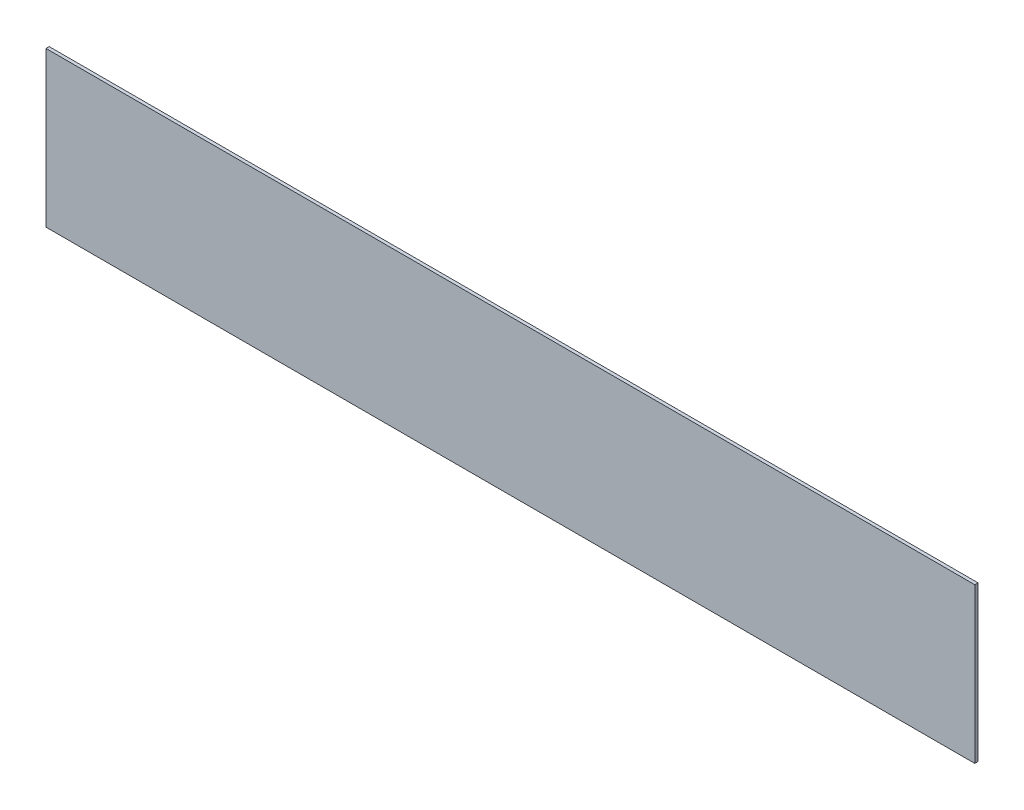
SolidWorks part; units mm, degrees
ref_plane "Front Plane" through (0, 0, 0) normal (0, 0, 1) x (1, 0, 0)
ref_plane "Top Plane" through (0, 0, 0) normal (0, 1, 0) x (1, 0, 0)
ref_plane "Right Plane" through (0, 0, 0) normal (1, 0, 0) x (0, 0, -1)
sketch "Sketch1" plane through (0, 0, 0) normal (0, 0, 1) x (1, 0, 0)
  line L1 (0, 0) -> (914.4, 0)
  line L2 (0, 0) -> (0, 152.4)
  line L3 (0, 152.4) -> (914.4, 152.4)
  line L4 (914.4, 0) -> (914.4, 152.4)
  dimension "D1" = 914.4
  dimension "D2" = 152.4
extrude "Boss-Extrude1" add sketch "Sketch1" along normal blind 3.175
